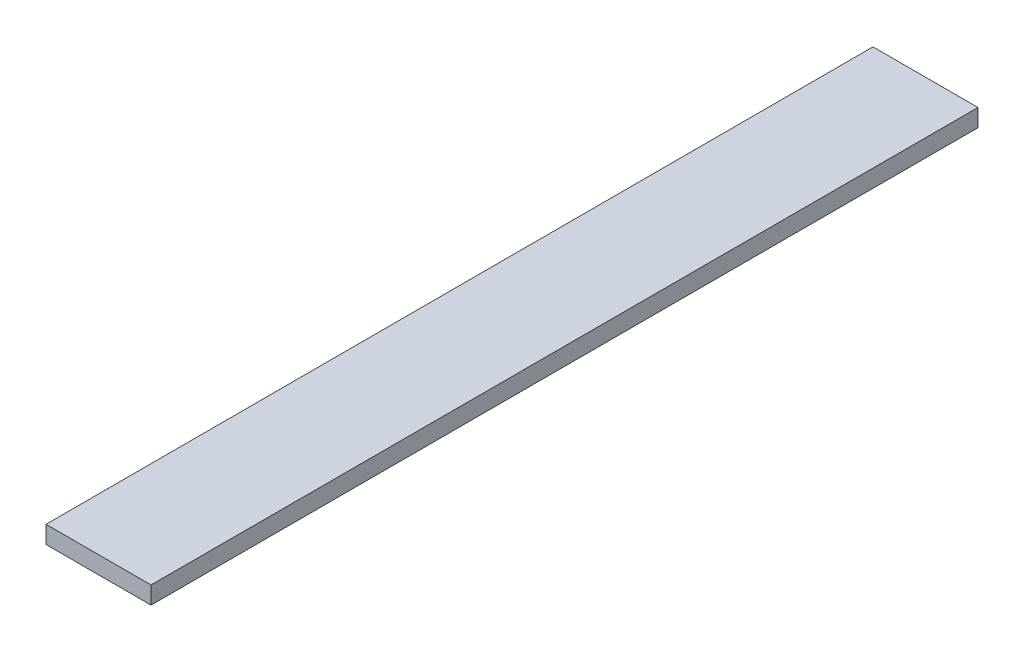
SolidWorks part; units mm, degrees
ref_plane "Front Plane" through (0, 0, 0) normal (0, 0, 1) x (1, 0, 0)
ref_plane "Top Plane" through (0, 0, 0) normal (0, 1, 0) x (1, 0, 0)
ref_plane "Right Plane" through (0, 0, 0) normal (1, 0, 0) x (0, 0, -1)
sketch "Sketch1" plane through (0, 0, 0) normal (0, 0, 1) x (1, 0, 0)
  line L1 (38.1, -6.35) -> (-38.1, -6.35)
  line L2 (38.1, -6.35) -> (38.1, 6.35)
  line L3 (38.1, 6.35) -> (-38.1, 6.35)
  line L4 (-38.1, -6.35) -> (-38.1, 6.35)
  line L5 (0, 6.35) -> (0, -6.35) construction
  line L6 (38.1, 0) -> (-38.1, 0) construction
  point P0 (0, 0)
  dimension "D1" = 12.7
  dimension "D2" = 76.2
extrude "Boss-Extrude1" add sketch "Sketch1" along normal blind 600
